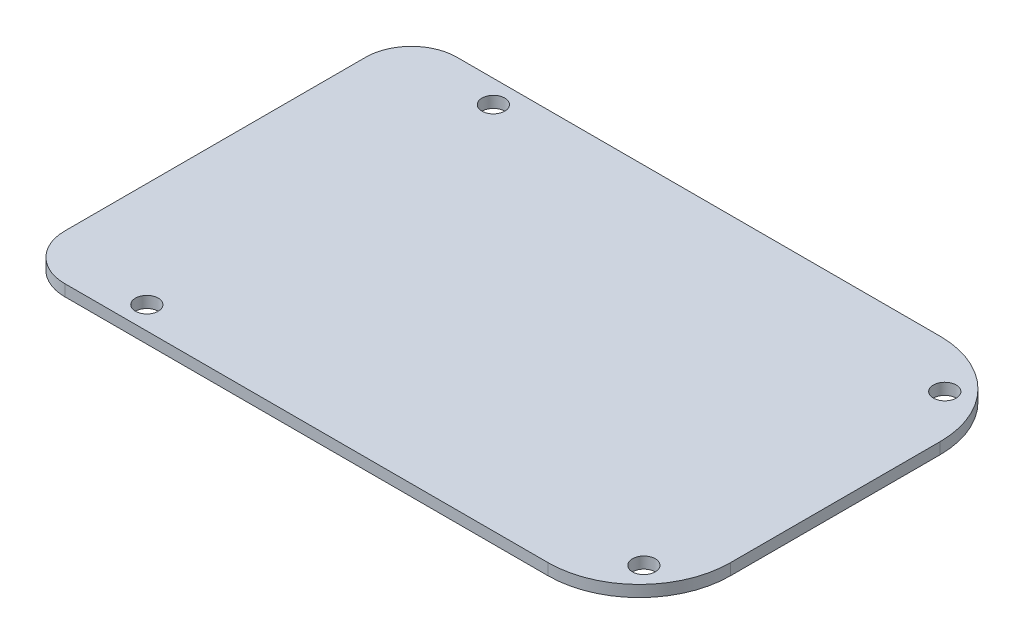
SolidWorks part; units mm, degrees
ref_plane "Front Plane" through (0, 0, 0) normal (0, 0, 1) x (1, 0, 0)
ref_plane "Top Plane" through (0, 0, 0) normal (0, 1, 0) x (1, 0, 0)
ref_plane "Right Plane" through (0, 0, 0) normal (1, 0, 0) x (0, 0, -1)
sketch "Sketch1" plane through (0, 0, 0) normal (0, 1, 0) x (1, 0, 0)
  line L1 (-36.83, 27.305) -> (30.48, 27.305)
  line L2 (-43.18, 20.955) -> (-43.18, -20.955)
  line L3 (-36.83, -27.305) -> (30.48, -27.305)
  line L4 (43.18, 14.605) -> (43.18, -14.605)
  line L5 (-43.18, 27.305) -> (43.18, -27.305) construction
  line L6 (-43.18, -27.305) -> (43.18, 27.305) construction
  circle A0 centre (-28.575, 24.13) radius 1.5875
  circle A1 centre (-28.575, -24.13) radius 1.5875
  circle A2 centre (37.465, -20.955) radius 1.5875
  circle A3 centre (37.465, 20.955) radius 1.5875
  arc A4 (-36.83, -27.305) -> (-43.18, -20.955) centre (-36.83, -20.955) cw
  arc A5 (-43.18, 20.955) -> (-36.83, 27.305) centre (-36.83, 20.955) cw
  arc A6 (30.48, -27.305) -> (43.18, -14.605) centre (30.48, -14.605) ccw
  arc A7 (43.18, 14.605) -> (30.48, 27.305) centre (30.48, 14.605) ccw
  point P0 (0, 0)
  dimension "D9" = 3.175
  dimension "D10" = 6.35
  dimension "D11" = 12.7
  dimension "D1" = 86.36
  dimension "D2" = 54.61
  dimension "D3" = 3.175
  dimension "D4" = 51.435
  dimension "D5" = 6.35
  dimension "D6" = 48.26
  dimension "D7" = 14.605
  dimension "D8" = 80.645
extrude "Boss-Extrude1" add sketch "Sketch1" along normal blind 1.5875
